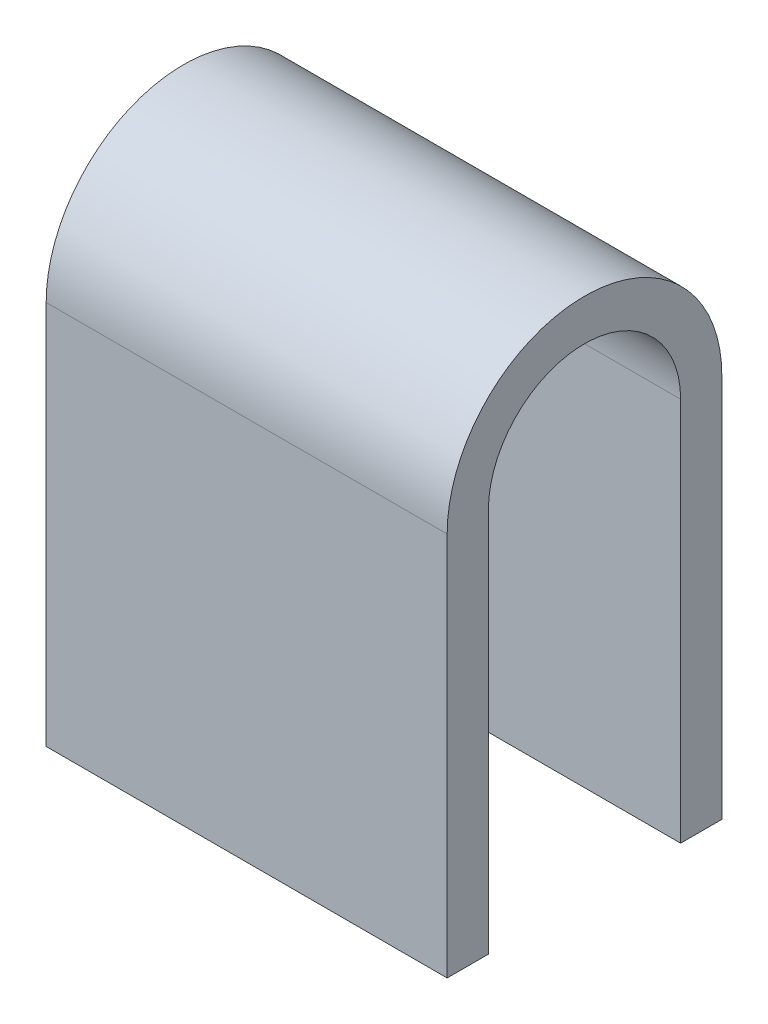
SolidWorks part; units mm, degrees
ref_plane "Front Plane" through (0, 0, 0) normal (0, 0, 1) x (1, 0, 0)
ref_plane "Top Plane" through (0, 0, 0) normal (0, 1, 0) x (1, 0, 0)
ref_plane "Right Plane" through (0, 0, 0) normal (1, 0, 0) x (0, 0, -1)
sketch "Sketch1" plane through (0, 0, 0) normal (0, 0, 1) x (1, 0, 0)
  line L1 (-9.271, -8.89) -> (9.271, -8.89)
  line L2 (-9.271, -8.89) -> (-9.271, 8.89)
  line L3 (-9.271, 8.89) -> (9.271, 8.89)
  line L4 (9.271, -8.89) -> (9.271, 8.89)
  line L5 (-9.271, -8.89) -> (9.271, 8.89) construction
  line L6 (-9.271, 8.89) -> (9.271, -8.89) construction
  point P0 (0, 0)
  dimension "D1" = 17.78
  dimension "D2" = 18.542
ref_plane "Plane2" through (0, 0, -12.7) normal (0, 0, 1) x (1, 0, 0)
sketch "Sketch4" plane through (0, 0, -12.7) normal (0, 0, 1) x (1, 0, 0)
  line L1 (9.271, -8.89) -> (-9.271, -8.89)
  line L2 (9.271, -8.89) -> (9.271, 8.89)
  line L3 (9.271, 8.89) -> (-9.271, 8.89)
  line L4 (-9.271, -8.89) -> (-9.271, 8.89)
  line L5 (9.271, -8.89) -> (-9.271, 8.89) construction
  line L6 (9.271, 8.89) -> (-9.271, -8.89) construction
  point P0 (0, 0)
extrude "Boss-Extrude4" add sketch "Sketch1" against normal blind 1.905
extrude "Boss-Extrude5" add sketch "Sketch4" along normal blind 1.905 separate body
ref_plane "Plane3" through (0, 0, -6.35) normal (0, 0, 1) x (1, 0, 0)
ref_plane "Plane4" through (0, 8.89, 0) normal (0, 1, 0) x (1, 0, 0)
ref_plane "Plane5" through (-9.271, 0, 0) normal (-1, 0, 0) x (0, 0, 1)
sketch "Sketch6" plane through (-9.271, 0, 0) normal (-1, 0, 0) x (0, 0, 1)
  line L0 (-12.7, 0) -> (0, 0) construction
  line L1 (-12.7, -5.4994) -> (-12.7, 5.4994) construction
  line L2 (-1.905, 8.89) -> (-1.905, -8.89) construction
  line L3 (10.1981, 8.89) -> (-10.1981, 8.89) construction
  line L4 (-6.35, 8.89) -> (-6.35, 7.62) construction
  line L5 (-10.795, 8.89) -> (-12.7, 8.89) construction
  line L6 (-12.7, 8.89) -> (-10.795, 8.89)
  line L7 (-1.905, 8.89) -> (0, 8.89)
  arc A0 (-10.795, 8.89) -> (-1.905, 8.89) centre (-6.35, 8.89) cw
  arc A1 (0, 8.89) -> (-12.7, 8.89) centre (-6.35, 8.89) ccw
extrude "Boss-Extrude6" add sketch "Sketch6" against normal up to surface (18.542 mm away) up to face at (9.271, 0, -0.9525)
